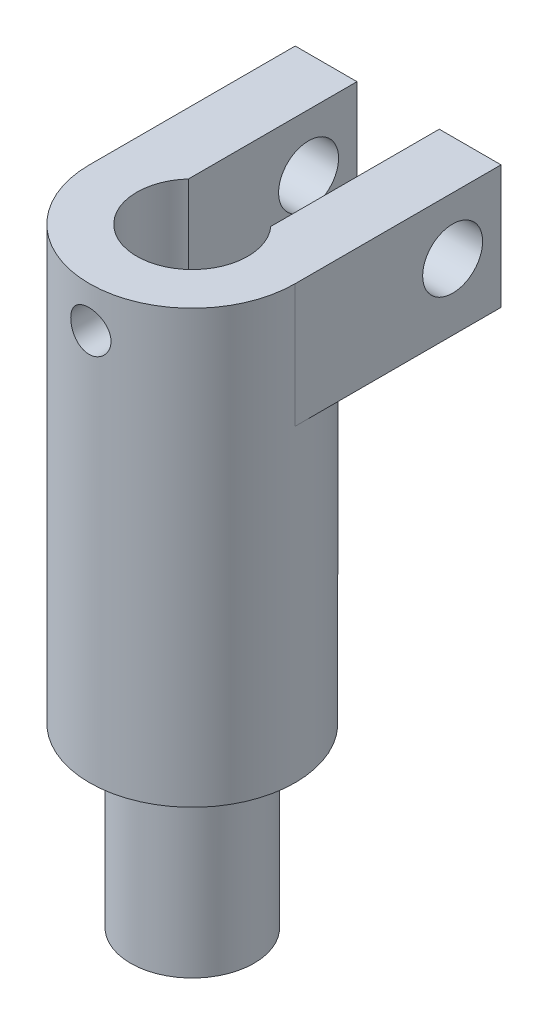
SolidWorks part; units mm, degrees
ref_plane "Front Plane" through (0, 0, 0) normal (0, 0, 1) x (1, 0, 0)
ref_plane "Top Plane" through (0, 0, 0) normal (0, 1, 0) x (1, 0, 0)
ref_plane "Right Plane" through (0, 0, 0) normal (1, 0, 0) x (0, 0, -1)
sketch "Sketch1" plane through (0, 0, 0) normal (0, 1, 0) x (1, 0, 0)
  circle A0 centre (0, 0) radius 3.429
  circle A1 centre (0, 0) radius 6.35
  dimension "D1" = 6.858
  dimension "D2" = 12.7
extrude "Boss-Extrude1" add sketch "Sketch1" along normal blind 19.05
sketch "Sketch2" plane through (0, 0, 0) normal (0, -1, 0) x (1, 0, 0)
  circle A0 centre (0, 0) radius 3.81
  dimension "D1" = 7.62
extrude "Boss-Extrude2" add sketch "Sketch2" along normal blind 10.922
sketch "Sketch3" plane through (0, 19.05, 0) normal (0, 1, 0) x (1, 0, 0)
  line L0 (6.35, 0) -> (6.35, 12.7)
  line L1 (6.35, 12.7) -> (2.54, 12.7)
  line L2 (2.54, 12.7) -> (2.54, 5.8199)
  line L3 (0, 0) -> (0, 9.6885) construction
  line L4 (-2.54, 5.8199) -> (-2.54, 2.3036)
  line L5 (-2.54, 12.7) -> (-2.54, 5.8199)
  line L6 (-6.35, 12.7) -> (-2.54, 12.7)
  line L7 (2.54, 5.8199) -> (2.54, 2.3036)
  line L8 (-6.35, 0) -> (-6.35, 12.7)
  circle A0 centre (0, 0) radius 3.429
  circle A1 centre (0, 0) radius 6.35
  circle M2 centre (0, 0) radius 6.35
  circle M3 centre (0, 0) radius 3.429
  dimension "D1" = 6.858
  dimension "D2" = 12.7
  dimension "D3" = 12.7
  dimension "D4" = 3.81
extrude "Boss-Extrude3" add sketch "Sketch3" along normal blind 7.62 contours A1 L7 L4 M3 | L1 L2 L0 M2 | A1 L0 L2 M2 | A1 L5 L8 M2 | L8 L5 L6 M2
hole_wizard "M3 Clearance Hole1" positions "Sketch4" profile "Sketch5" hole size "M3" standard "ANSI Metric"
sketch "Sketch4" plane through (-6.35, 0, 0) normal (-1, 0, 0) x (0, 0, 1)
  point P0 (-9.7141, 23.1515)
  point P1 (-9.7141, 23.1515)
sketch "Sketch5" plane through (-6.35, 23.1515, -9.7141) normal (0, 1, 0) x (0, 0, 1)
  line L0 (0, 0) -> (0, 26.5116)
  line L1 (0, 26.5116) -> (1.85, 25.4)
  line L2 (1.85, 25.4) -> (1.85, 0)
  line L5 (1.85, 0) -> (0, 0)
  line L10 (0, 26.5116) -> (-1.85, 25.4) construction
  line L11 (0, -6.35) -> (0, 107.95) construction
  dimension "Hole Dia." = 3.7
  dimension "Hole Depth" = 25.4
  dimension "Drill Angle" = 118
sketch "Sketch6" plane through (0, 0, 0) normal (0, -1, 0) x (1, 0, 0)
  circle A0 centre (0, 0) radius 8.89
  dimension "D1" = 17.78
curve "Helix/Spiral1" pitch 1.76 height 14.96 turns 8.5
sketch "Sketch7" plane through (0, 26.67, 0) normal (0, 1, 0) x (1, 0, 0)
  line L0 (2.54, 5.8199) -> (2.54, 2.3036)
  line L1 (-2.54, 5.8199) -> (-2.54, 2.3036)
  circle A0 centre (0, 0) radius 3.429 construction
  circle A1 centre (0, 0) radius 3.429
  arc M2 (2.54, 5.8199) -> (-2.54, 5.8199) centre (0, 0) ccw
  circle M9 centre (0, 0) radius 3.429
extrude "Cut-Extrude1" cut sketch "Sketch7" against normal blind 8.89 contours L1 L0 M2 M9
hole_wizard "Tap Drill for M3x0.5 Tap1" positions "3DSketch1" profile "Sketch8" hole size "M3x0.5" standard "ANSI Metric" end condition through all
sketch3d "3DSketch1"
  point P0 (-0.0338, 24.1306, 6.3499)
sketch "Sketch8" plane through (-0.0338, 24.1306, 6.3499) normal (0, 1, 0) x (1, 0, 0.0053)
  line L0 (0, 0) -> (0, 19.0836)
  line L1 (0, 19.0836) -> (1.25, 19.0836)
  line L2 (1.25, 19.0836) -> (1.25, 0)
  line L5 (1.25, 0) -> (0, 0)
  line L11 (0, -6.35) -> (0, 107.95) construction
  dimension "Thru Hole Dia." = 2.5
  dimension "Thru Hole Depth" = 19.0836
sketch "Sketch9" plane through (0, 0, 0) normal (0, 1, 0) x (1, 0, 0)
  circle A0 centre (0, 0) radius 3.429
  dimension "D1" = 6.858
